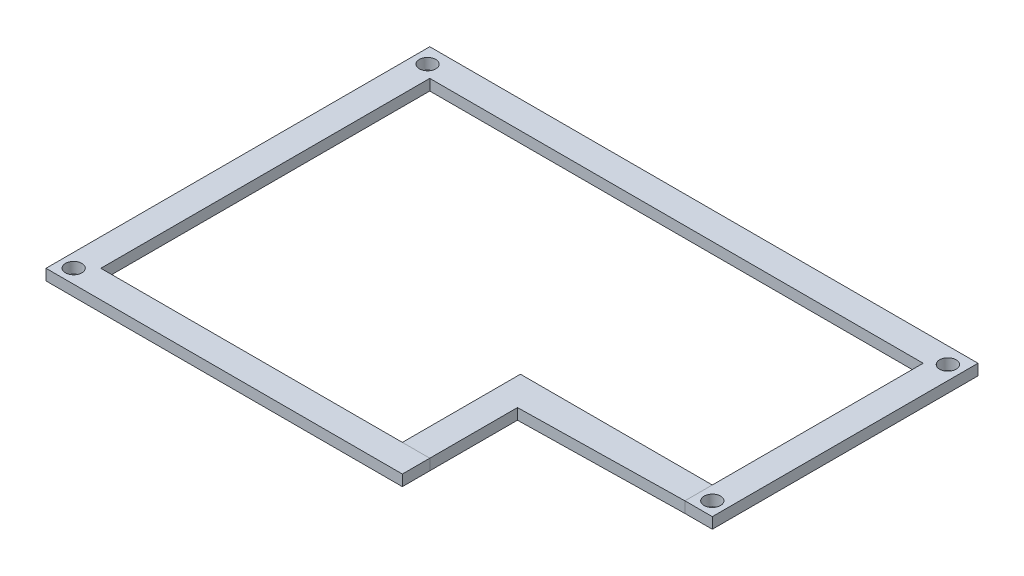
SolidWorks part; units mm, degrees
ref_plane "Front Plane" through (0, 0, 0) normal (0, 0, 1) x (1, 0, 0)
ref_plane "Top Plane" through (0, 0, 0) normal (0, 1, 0) x (1, 0, 0)
ref_plane "Right Plane" through (0, 0, 0) normal (1, 0, 0) x (0, 0, -1)
sketch "Sketch1" plane through (0, 0, 0) normal (0, 1, 0) x (1, 0, 0)
  line L1 (-50, 35) -> (50, 35)
  line L2 (-50, 35) -> (-50, -35)
  line L3 (-50, -35) -> (50, -35)
  line L4 (50, 35) -> (50, -35)
  line L5 (-50, 35) -> (50, -35) construction
  line L6 (-50, -35) -> (50, 35) construction
  line L7 (-45, 30) -> (45, 30)
  line L8 (-45, 30) -> (-45, -30)
  line L9 (-45, -30) -> (45, -30)
  line L10 (45, 30) -> (45, -30)
  line L11 (-45, 30) -> (45, -30) construction
  line L12 (-45, -30) -> (45, 30) construction
  point P0 (0, 0)
  point P6 (0, 0)
  dimension "D1" = 100
  dimension "D2" = 70
  dimension "D3" = 90
  dimension "D4" = 60
extrude "Boss-Extrude1" add sketch "Sketch1" along normal blind 2
sketch "Sketch2" plane through (0, 2, 0) normal (0, 1, 0) x (1, 0, 0)
  line L0 (-50, 35) -> (-50, -35) construction
  line L1 (50, -35) -> (15, -35)
  line L2 (50, -35) -> (50, -13.46)
  line L3 (50, -13.46) -> (15, -13.46)
  line L4 (15, -35) -> (15, -13.46)
  line L5 (50, 35) -> (-50, 35) construction
  dimension "D1" = 65
  dimension "D2" = 48.46
extrude "Cut-Extrude1" cut sketch "Sketch2" against normal blind 2
sketch "Sketch3" plane through (0, 2, 0) normal (0, 1, 0) x (1, 0, 0)
  line L0 (15, -30) -> (15, -14)
  line L1 (15, -14) -> (45, -13.46)
  line L2 (45, -13.46) -> (45, -8.46)
  line L3 (45, -13.46) -> (45, 30) construction
  line L4 (45, -8.46) -> (10, -8.46)
  line L5 (10, -8.46) -> (10, -30)
  line L6 (-45, -30) -> (15, -30) construction
  line L7 (10, -30) -> (15, -30)
  point P12 (15, -14)
  dimension "D1" = 5
  dimension "D2" = 5
extrude "Boss-Extrude2" add sketch "Sketch3" against normal blind 2 separate body
sketch "Sketch4" plane through (0, 2, 0) normal (0, 1, 0) x (1, 0, 0)
  line L0 (50, 35) -> (-50, 35) construction
  line L1 (-50, 35) -> (-50, -35) construction
  line L2 (50, -13.46) -> (50, 35) construction
  line L3 (50, -13.46) -> (45, -13.46) construction
  line L5 (-50, -35) -> (15, -35) construction
  circle A0 centre (-47.45, 32.05) radius 1.5
  circle A1 centre (47.45, 32.05) radius 1.5
  circle A2 centre (47.5, -10.96) radius 1.5
  circle A3 centre (-47.5, -32.45) radius 1.5
  dimension "D3" = 3
  dimension "D4" = 3
  dimension "D7" = 3
  dimension "D9" = 3
  dimension "D1" = 2.95
  dimension "D2" = 2.55
  dimension "D5" = 2.95
  dimension "D6" = 2.55
  dimension "D8" = 2.5
  dimension "D10" = 2.55
extrude "Cut-Extrude2" cut sketch "Sketch4" against normal blind 2
